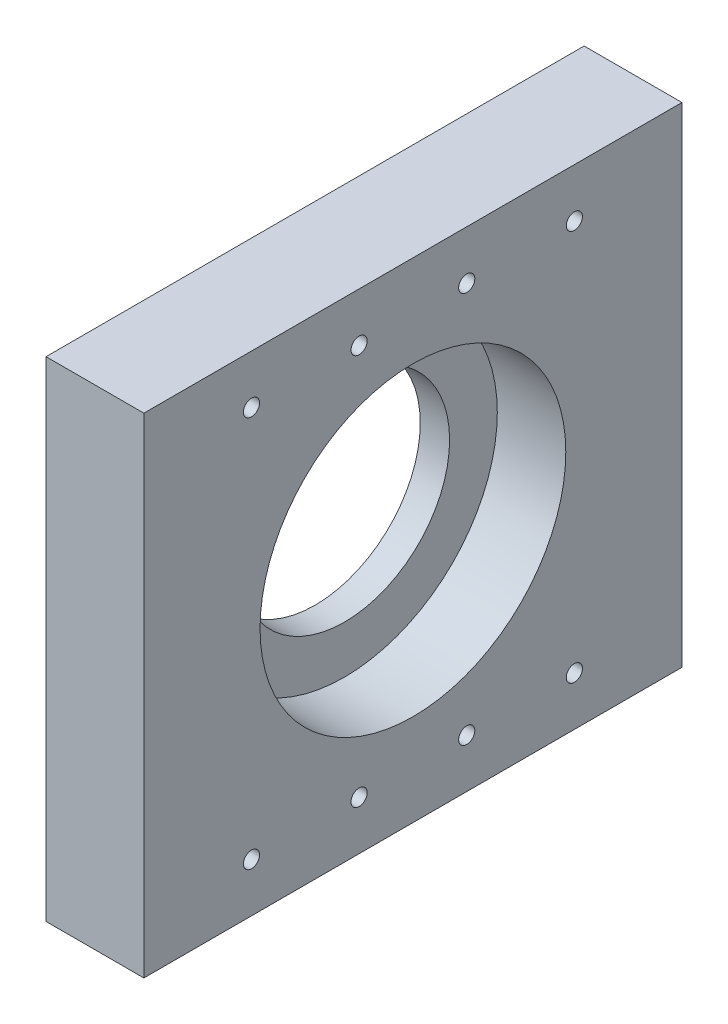
SolidWorks part; units mm, degrees
ref_plane "前视基准面" through (0, 0, 0) normal (0, 0, 1) x (1, 0, 0)
ref_plane "上视基准面" through (0, 0, 0) normal (0, 1, 0) x (1, 0, 0)
ref_plane "右视基准面" through (0, 0, 0) normal (1, 0, 0) x (0, 0, -1)
other "Configuration Table"
sketch "草图1" plane through (0, 0, 0) normal (1, 0, 0) x (0, 0, -1)
  line L1 (-55, 50) -> (55, 50)
  line L2 (-55, 50) -> (-55, -50)
  line L3 (-55, -50) -> (55, -50)
  line L4 (55, 50) -> (55, -50)
  line L5 (-55, 50) -> (55, -50) construction
  line L6 (-55, -50) -> (55, 50) construction
  point P0 (0, 0)
  dimension "D1" = 110
  dimension "D2" = 100
extrude "凸台-拉伸1" add sketch "草图1" along normal blind 20
sketch "草图2" plane through (20, 0, 0) normal (1, 0, 0) x (0, 0, -1)
  circle A0 centre (0, 0) radius 31.25
  dimension "D1" = 62.5
extrude "切除-拉伸1" cut sketch "草图2" against normal blind 14
sketch "草图3" plane through (6, 0, 0) normal (1, 0, 0) x (0, 0, -1)
  circle A0 centre (0, 0) radius 21.5
  dimension "D1" = 43
extrude "切除-拉伸2" cut sketch "草图3" against normal blind 14
sketch "草图4" plane through (20, 0, 0) normal (1, 0, 0) x (0, 0, -1)
  line L0 (0, 0) -> (65.0526, 0) construction
  line L1 (55, 50) -> (-55, 50) construction
  line L2 (55, -50) -> (55, 50) construction
  circle A0 centre (33, 40) radius 1.65
  circle A1 centre (11, 40) radius 1.65
  circle A2 centre (-11, 40) radius 1.65
  circle A3 centre (-33, 40) radius 1.65
  circle A5 centre (-11, -40) radius 1.65
  circle A6 centre (11, -40) radius 1.65
  circle A7 centre (33, -40) radius 1.65
  circle A8 centre (-33, -40) radius 1.65
  dimension "D7" = 3.3
  dimension "D5" = 3.3
  dimension "D8" = 3.3
  dimension "D9" = 3.3
  dimension "D1" = 10
  dimension "D2" = 22
  dimension "D3" = 22
  dimension "D4" = 22
  dimension "D6" = 22
extrude "切除-拉伸3" cut sketch "草图4" against normal through all
